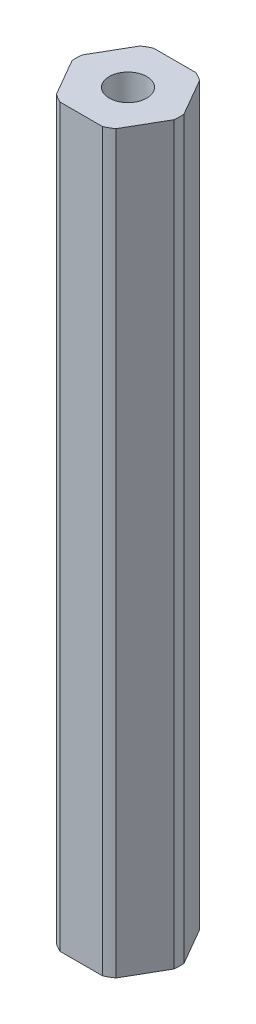
SolidWorks part; units mm, degrees
material "6061-T6 (SS)"
ref_plane "Front" through (0, 0, 0) normal (0, 0, 1) x (1, 0, 0)
ref_plane "Top" through (0, 0, 0) normal (0, 1, 0) x (1, 0, 0)
ref_plane "Right" through (0, 0, 0) normal (1, 0, 0) x (0, 0, -1)
sketch "Sketch1" plane through (0, 0, 0) normal (0, 1, 0) x (1, 0, 0)
  line L1 (3.6662, -6.35) -> (7.3323, 0)
  line L2 (7.3323, 0) -> (3.6662, 6.35)
  line L3 (3.6662, 6.35) -> (-3.6662, 6.35)
  line L4 (-3.6662, 6.35) -> (-7.3323, 0)
  line L5 (-7.3323, 0) -> (-3.6662, -6.35)
  line L6 (-3.6662, -6.35) -> (3.6662, -6.35)
  circle A0 centre (0, 0) radius 6.35 construction
  circle A1 centre (0, 0) radius 2.5527
  circle A2 centre (0, 0) radius 6.9787
  dimension "D1" = 12.7
  dimension "D2" = 5.1054
  dimension "D3" = 13.9573
extrude "Boss-Extrude1" add sketch "Sketch1" along normal mid plane 100.0125 contours L6 A2 L1 L2 L3 L4 L5 A1
